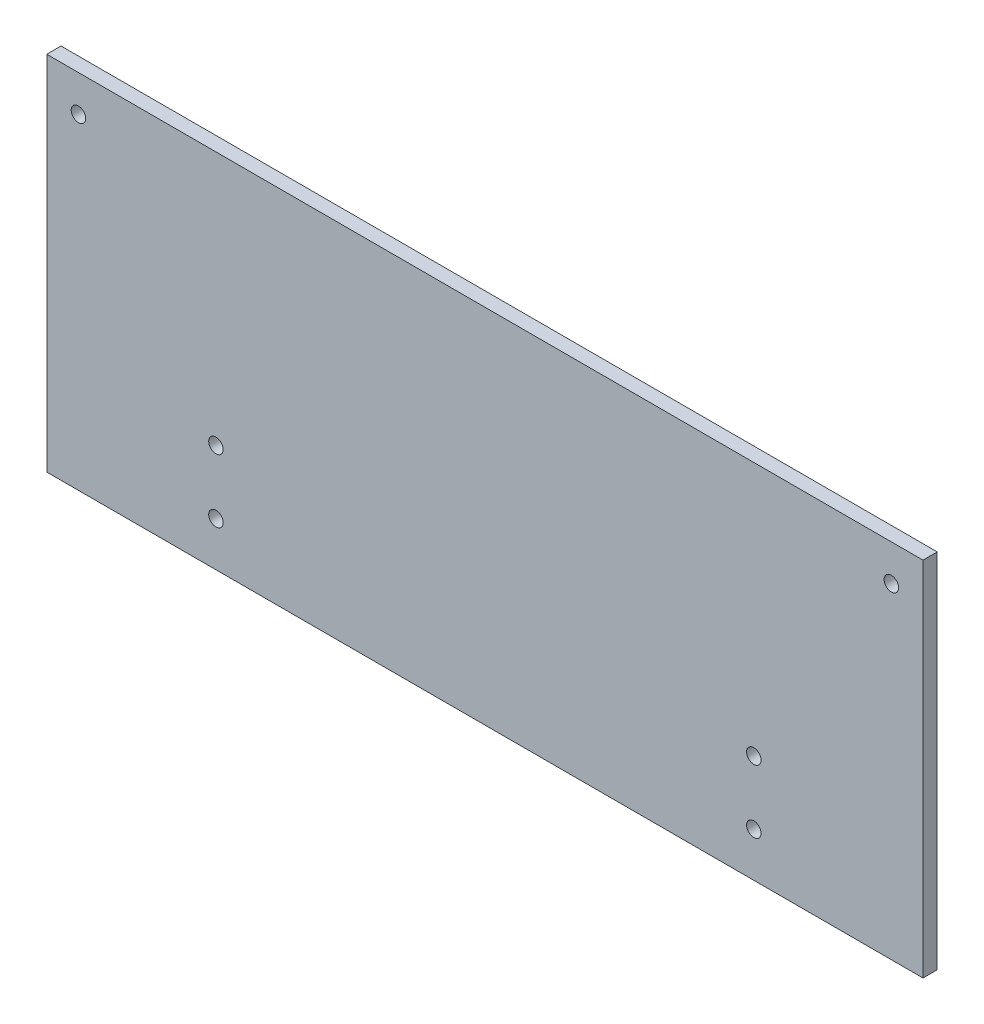
SolidWorks part; units mm, degrees
ref_plane "Front Plane" through (0, 0, 0) normal (0, 0, 1) x (1, 0, 0)
ref_plane "Top Plane" through (0, 0, 0) normal (0, 1, 0) x (1, 0, 0)
ref_plane "Right Plane" through (0, 0, 0) normal (1, 0, 0) x (0, 0, -1)
sketch "Sketch1" plane through (0, 0, 0) normal (0, 0, 1) x (1, 0, 0)
  line L5 (4, 101.6) -> (250, 101.6)
  line L6 (241.11, 101.6) -> (241.11, 91.44) construction
  line L23 (250, 101.6) -> (222.314, 101.6) construction
  line L32 (127, 101.6) -> (127, 0) construction
  line L33 (127, 0) -> (250, 0)
  line L34 (127, 0) -> (4, 0)
  line L35 (4, 0) -> (4, 101.6)
  line L36 (250, 0) -> (250, 101.6)
  line L37 (250, 0) -> (228.664, 0) construction
  circle A8 centre (51.498, 12.446) radius 2.032
  circle A9 centre (51.498, 30.226) radius 2.032
  circle A10 centre (202.502, 30.226) radius 2.032
  circle A11 centre (202.502, 12.446) radius 2.032
  circle A12 centre (241.11, 91.44) radius 2.032
  circle A13 centre (12.89, 91.44) radius 2.032
  dimension "D1" = 246
  dimension "D5" = 47.498
  dimension "D8" = 8.89
  dimension "D9" = 8.89
  dimension "D3" = 17.78
  dimension "D2" = 101.6
  dimension "D4" = 47.498
  dimension "D6" = 12.446
  dimension "D7" = 10.16
  dimension "D10" = 10.16
  dimension "D14" = 17.78
  dimension "D15" = 12.446
extrude "Boss-Extrude1" add sketch "Sketch1" along normal blind 4
